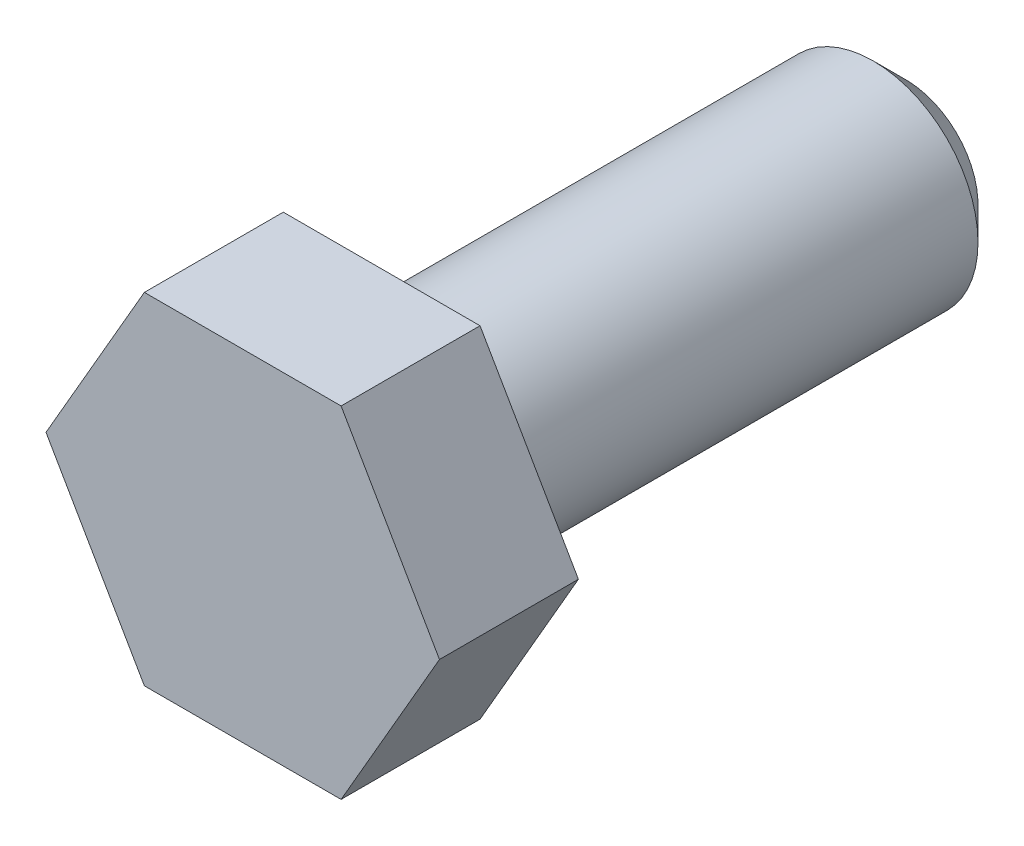
SolidWorks part; units mm, degrees
ref_plane "Plane1" through (0, 0, 0) normal (0, 0, 1) x (1, 0, 0)
ref_plane "MSC_PF1" through (0, 0, 0) normal (0, 1, 0) x (1, 0, 0)
ref_plane "Plane3" through (0, 0, 0) normal (1, 0, 0) x (0, 0, -1)
sketch "Sketch1" plane through (0, 0, 0) normal (0, 0, 1) x (1, 0, 0)
  line L0 (0, 0) -> (1, 0) construction
  line L1 (-3.7528, 6.5) -> (3.7528, 6.5)
  line L2 (-3.7528, -6.5) -> (3.7528, -6.5)
  line L3 (3.7528, 6.5) -> (7.5056, 0)
  line L4 (7.5056, 0) -> (3.7528, -6.5)
  line L5 (-3.7528, 6.5) -> (-7.5056, 0)
  line L6 (-7.5056, 0) -> (-3.7528, -6.5)
  circle A0 centre (0, 0) radius 6.5 construction
  dimension "P" = 1
  dimension "s" = 13
extrude "Base-Extrude" add sketch "Sketch1" along normal blind 5.3
sketch "Sketch3" plane through (0, 0, 0) normal (0, 0, -1) x (-1, 0, 0)
  circle A0 centre (0, 0) radius 4
  dimension "_d" = 8
extrude "Boss-Extrude1" add sketch "Sketch3" along normal blind 20
cosmetic thread "Условное изображение резьбы2" parameters "D2"=7
chamfer "Chamfer1" distance 1.25 angle 45 1 edges at (-4, 0, -20)
